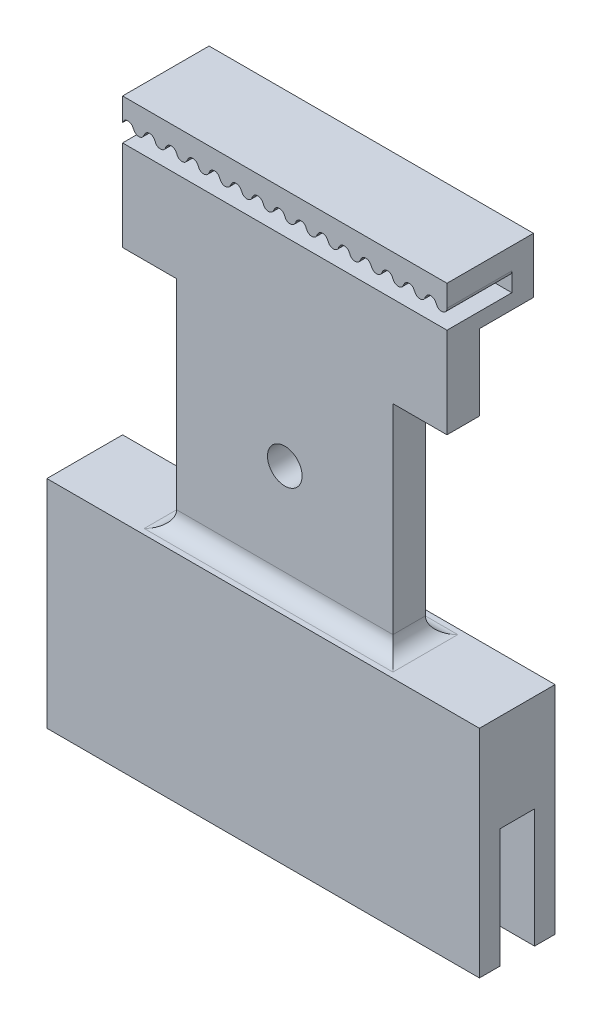
SolidWorks part; units mm, degrees
ref_plane "Ön Düzlem" through (0, 0, 0) normal (0, 0, 1) x (1, 0, 0)
ref_plane "Üst Düzlem" through (0, 0, 0) normal (0, 1, 0) x (1, 0, 0)
ref_plane "Sağ Düzlem" through (0, 0, 0) normal (1, 0, 0) x (0, 0, -1)
sketch "Çizim1" plane through (0, 0, 0) normal (0, 1, 0) x (1, 0, 0)
  line L1 (-20, -3.5) -> (20, -3.5)
  line L2 (-20, -3.5) -> (-20, 3.5)
  line L3 (-20, 3.5) -> (20, 3.5)
  line L4 (20, -3.5) -> (20, 3.5)
  line L5 (-20, -3.5) -> (20, 3.5) construction
  line L6 (-20, 3.5) -> (20, -3.5) construction
  point P1 (0, 0)
  dimension "D1" = 40
  dimension "D2" = 7
extrude "Yükseklik-Ekstrüzyon1" add sketch "Çizim1" against normal blind 20
sketch "Çizim2" plane through (0, -20, 0) normal (0, -1, 0) x (1, 0, 0)
  line L0 (20, 3.5) -> (20, -3.5) construction
  line L1 (-20, -1.6) -> (20, -1.6)
  line L2 (-20, -1.6) -> (-20, 1.6)
  line L3 (-20, 1.6) -> (20, 1.6)
  line L4 (20, -1.6) -> (20, 1.6)
  line L5 (-20, -1.6) -> (20, 1.6) construction
  line L6 (-20, 1.6) -> (20, -1.6) construction
  point P0 (0, 0)
  dimension "D1" = 3.2
extrude "Kes-Ekstrüzyon1" cut sketch "Çizim2" against normal blind 11
sketch "Çizim4" plane through (0, 0, 0) normal (0, 0, 1) x (1, 0, 0)
  line L0 (0, 0) -> (-10, 0) construction
  line L1 (-20, 0) -> (20, 0) construction
  line L2 (0, 0) -> (10, 0) construction
  line L3 (0, 0) -> (0, 10) construction
  line L4 (-10, 0) -> (10, 0)
  line L5 (-10, 0) -> (-10, 20)
  line L6 (-10, 20) -> (10, 20)
  line L7 (10, 0) -> (10, 20)
  circle A0 centre (0, 10) radius 1.6
  dimension "D2" = 3.2
  dimension "D1" = 20
  dimension "D3" = 10
extrude "Yükseklik-Ekstrüzyon2" add sketch "Çizim4" along normal blind 1.5 and the other way blind 1.5
fillet "Radyus1" radius 1.5 4 edges at (-10, 0, 0) (0, 0, -1.5) (10, 0, 0) (0, 0, 1.5)
ref_plane "Düzlem1" through (0, 0, -1.5) normal (0, 0, -1) x (-1, 0, 0)
sketch "Çizim7" plane through (0, 20, 0) normal (0, 1, 0) x (1, 0, 0)
  line L1 (-15, -1.5) -> (15, -1.5)
  line L2 (-15, -1.5) -> (-15, 1.5)
  line L3 (-15, 1.5) -> (15, 1.5)
  line L4 (15, -1.5) -> (15, 1.5)
  line L5 (-15, -1.5) -> (15, 1.5) construction
  line L6 (-15, 1.5) -> (15, -1.5) construction
  point P0 (0, 0)
  dimension "D1" = 3
  dimension "D2" = 30
extrude "Yükseklik-Ekstrüzyon4" add sketch "Çizim7" along normal blind 7
sketch "Çizim9" plane through (0, 0, -1.5) normal (0, 0, -1) x (-1, 0, 0)
  line L0 (0, 32.14) -> (-15, 32.14)
  line L1 (0, 32.14) -> (15, 32.14)
  line L2 (-15, 32.14) -> (-15, 29.64)
  line L3 (15, 32.14) -> (15, 29.64)
  line L4 (-15, 29.64) -> (15, 29.64)
  line L5 (-15, 30.39) -> (-14, 30.39)
  line L6 (-15, 30.39) -> (-15, 30.13)
  line L7 (-14.51, 29.64) -> (-14.49, 29.64)
  line L8 (-14, 30.39) -> (-14, 30.13)
  line L9 (-13, 30.39) -> (-12, 30.39)
  line L10 (-12, 30.39) -> (-12, 30.13)
  line L11 (-12.51, 29.64) -> (-12.49, 29.64)
  line L12 (-13, 30.39) -> (-13, 30.13)
  line L13 (-11, 30.39) -> (-10, 30.39)
  line L14 (-10, 30.39) -> (-10, 30.13)
  line L15 (-10.51, 29.64) -> (-10.49, 29.64)
  line L16 (-11, 30.39) -> (-11, 30.13)
  line L17 (-9, 30.39) -> (-8, 30.39)
  line L18 (-8, 30.39) -> (-8, 30.13)
  line L19 (-8.51, 29.64) -> (-8.49, 29.64)
  line L20 (-9, 30.39) -> (-9, 30.13)
  line L21 (-7, 30.39) -> (-6, 30.39)
  line L22 (-6, 30.39) -> (-6, 30.13)
  line L23 (-6.51, 29.64) -> (-6.49, 29.64)
  line L24 (-7, 30.39) -> (-7, 30.13)
  line L25 (-5, 30.39) -> (-4, 30.39)
  line L26 (-4, 30.39) -> (-4, 30.13)
  line L27 (-4.51, 29.64) -> (-4.49, 29.64)
  line L28 (-5, 30.39) -> (-5, 30.13)
  line L29 (-3, 30.39) -> (-2, 30.39)
  line L30 (-2, 30.39) -> (-2, 30.13)
  line L31 (-2.51, 29.64) -> (-2.49, 29.64)
  line L32 (-3, 30.39) -> (-3, 30.13)
  line L33 (-1, 30.39) -> (0, 30.39)
  line L34 (0, 30.39) -> (0, 30.13)
  line L35 (-0.51, 29.64) -> (-0.49, 29.64)
  line L36 (-1, 30.39) -> (-1, 30.13)
  line L37 (1, 30.39) -> (2, 30.39)
  line L38 (2, 30.39) -> (2, 30.13)
  line L39 (1.49, 29.64) -> (1.51, 29.64)
  line L40 (1, 30.39) -> (1, 30.13)
  line L41 (3, 30.39) -> (4, 30.39)
  line L42 (4, 30.39) -> (4, 30.13)
  line L43 (3.49, 29.64) -> (3.51, 29.64)
  line L44 (3, 30.39) -> (3, 30.13)
  line L45 (5, 30.39) -> (6, 30.39)
  line L46 (6, 30.39) -> (6, 30.13)
  line L47 (5.49, 29.64) -> (5.51, 29.64)
  line L48 (5, 30.39) -> (5, 30.13)
  line L49 (7, 30.39) -> (8, 30.39)
  line L50 (8, 30.39) -> (8, 30.13)
  line L51 (7.49, 29.64) -> (7.51, 29.64)
  line L52 (7, 30.39) -> (7, 30.13)
  line L53 (9, 30.39) -> (10, 30.39)
  line L54 (10, 30.39) -> (10, 30.13)
  line L55 (9.49, 29.64) -> (9.51, 29.64)
  line L56 (9, 30.39) -> (9, 30.13)
  line L57 (11, 30.39) -> (12, 30.39)
  line L58 (12, 30.39) -> (12, 30.13)
  line L59 (11.49, 29.64) -> (11.51, 29.64)
  line L60 (11, 30.39) -> (11, 30.13)
  line L61 (13, 30.39) -> (14, 30.39)
  line L62 (14, 30.39) -> (14, 30.13)
  line L63 (13.49, 29.64) -> (13.51, 29.64)
  line L64 (13, 30.39) -> (13, 30.13)
  line L65 (-5.51, 30.39) -> (-5.49, 30.39)
  line L66 (-6, 29.9) -> (-6, 29.64)
  line L67 (-6, 29.64) -> (-5, 29.64)
  line L68 (-5, 29.9) -> (-5, 29.64)
  line L69 (-3.51, 30.39) -> (-3.49, 30.39)
  line L70 (-3, 29.9) -> (-3, 29.64)
  line L71 (-4, 29.64) -> (-3, 29.64)
  line L72 (-4, 29.9) -> (-4, 29.64)
  line L73 (-1.51, 30.39) -> (-1.49, 30.39)
  line L74 (-1, 29.9) -> (-1, 29.64)
  line L75 (-2, 29.64) -> (-1, 29.64)
  line L76 (-2, 29.9) -> (-2, 29.64)
  line L77 (0.49, 30.39) -> (0.51, 30.39)
  line L78 (1, 29.9) -> (1, 29.64)
  line L79 (0, 29.64) -> (1, 29.64)
  line L80 (0, 29.9) -> (0, 29.64)
  line L81 (2.49, 30.39) -> (2.51, 30.39)
  line L82 (3, 29.9) -> (3, 29.64)
  line L83 (2, 29.64) -> (3, 29.64)
  line L84 (2, 29.9) -> (2, 29.64)
  line L85 (4.49, 30.39) -> (4.51, 30.39)
  line L86 (5, 29.9) -> (5, 29.64)
  line L87 (4, 29.64) -> (5, 29.64)
  line L88 (4, 29.9) -> (4, 29.64)
  line L89 (6.49, 30.39) -> (6.51, 30.39)
  line L90 (7, 29.9) -> (7, 29.64)
  line L91 (6, 29.64) -> (7, 29.64)
  line L92 (6, 29.9) -> (6, 29.64)
  line L93 (8.49, 30.39) -> (8.51, 30.39)
  line L94 (9, 29.9) -> (9, 29.64)
  line L95 (8, 29.64) -> (9, 29.64)
  line L96 (8, 29.9) -> (8, 29.64)
  line L97 (10.49, 30.39) -> (10.51, 30.39)
  line L98 (11, 29.9) -> (11, 29.64)
  line L99 (10, 29.64) -> (11, 29.64)
  line L100 (10, 29.9) -> (10, 29.64)
  line L101 (12.49, 30.39) -> (12.51, 30.39)
  line L102 (13, 29.9) -> (13, 29.64)
  line L103 (12, 29.64) -> (13, 29.64)
  line L104 (12, 29.9) -> (12, 29.64)
  line L105 (14.49, 30.39) -> (14.51, 30.39)
  line L106 (15, 29.9) -> (15, 29.64)
  line L107 (14, 29.64) -> (15, 29.64)
  line L108 (14, 29.9) -> (14, 29.64)
  line L109 (-7.51, 30.39) -> (-7.49, 30.39)
  line L110 (-7, 29.9) -> (-7, 29.64)
  line L111 (-8, 29.64) -> (-7, 29.64)
  line L112 (-8, 29.9) -> (-8, 29.64)
  line L113 (-9.51, 30.39) -> (-9.49, 30.39)
  line L114 (-9, 29.9) -> (-9, 29.64)
  line L115 (-10, 29.64) -> (-9, 29.64)
  line L116 (-10, 29.9) -> (-10, 29.64)
  line L117 (-11.51, 30.39) -> (-11.49, 30.39)
  line L118 (-11, 29.9) -> (-11, 29.64)
  line L119 (-12, 29.64) -> (-11, 29.64)
  line L120 (-12, 29.9) -> (-12, 29.64)
  line L121 (-13.51, 30.39) -> (-13.49, 30.39)
  line L122 (-13, 29.9) -> (-13, 29.64)
  line L123 (-14, 29.64) -> (-13, 29.64)
  line L124 (-14, 29.9) -> (-14, 29.64)
  line L125 (-13.9826, 30.0293) -> (-14.0105, 30.0293)
  line L126 (-11.9826, 30.0293) -> (-12.0105, 30.0293)
  line L127 (-9.9826, 30.0293) -> (-10.0105, 30.0293)
  line L128 (-7.9826, 30.0293) -> (-8.0105, 30.0293)
  line L129 (-5.9826, 30.0293) -> (-6.0105, 30.0293)
  line L130 (-3.9826, 30.0293) -> (-4.0105, 30.0293)
  line L131 (-1.9826, 30.0293) -> (-2.0105, 30.0293)
  line L132 (0.0174, 30.0293) -> (-0.0105, 30.0293)
  line L133 (2.0174, 30.0293) -> (1.9895, 30.0293)
  line L134 (4.0174, 30.0293) -> (3.9895, 30.0293)
  line L135 (6.0174, 30.0293) -> (5.9895, 30.0293)
  line L136 (8.0174, 30.0293) -> (7.9895, 30.0293)
  line L137 (10.0174, 30.0293) -> (9.9895, 30.0293)
  line L138 (12.0174, 30.0293) -> (11.9895, 30.0293)
  line L139 (14.0174, 30.0293) -> (13.9895, 30.0293)
  line L140 (-13.0174, 30.0293) -> (-12.9895, 30.0293)
  line L141 (-11.0174, 30.0293) -> (-10.9895, 30.0293)
  line L142 (-9.0174, 30.0293) -> (-8.9895, 30.0293)
  line L143 (-7.0174, 30.0293) -> (-6.9895, 30.0293)
  line L144 (-5.0174, 30.0293) -> (-4.9895, 30.0293)
  line L145 (-3.0174, 30.0293) -> (-2.9895, 30.0293)
  line L146 (-1.0174, 30.0293) -> (-0.9895, 30.0293)
  line L147 (0.9826, 30.0293) -> (1.0105, 30.0293)
  line L148 (2.9826, 30.0293) -> (3.0105, 30.0293)
  line L149 (4.9826, 30.0293) -> (5.0105, 30.0293)
  line L150 (6.9826, 30.0293) -> (7.0105, 30.0293)
  line L151 (8.9826, 30.0293) -> (9.0105, 30.0293)
  line L152 (10.9826, 30.0293) -> (11.0105, 30.0293)
  line L153 (12.9826, 30.0293) -> (13.0105, 30.0293)
  line L154 (14.9826, 30.0293) -> (15.0105, 30.0293)
  line L155 (-15, 27) -> (-15, 28.38)
  line L156 (0, 27) -> (-15, 27)
  line L157 (0, 27) -> (15, 27)
  line L158 (15, 27) -> (15, 28.38)
  line L159 (-15, 28.38) -> (15, 28.38)
  line L160 (-16.7921, 31.51) -> (-16.7921, 27) construction
  line L161 (-15, 28.38) -> (-16.7921, 28.38) construction
  line L162 (-17.2226, 28.38) -> (-17.2226, 30.58) construction
  line L163 (-17.2226, 30.58) -> (18.4338, 30.58) construction
  line L164 (16.139, 30.58) -> (16.139, 28.38) construction
  line L165 (16.6815, 28.38) -> (16.6815, 30.48) construction
  arc A0 (-14.49, 29.64) -> (-14, 30.13) centre (-14.49, 30.13) ccw
  arc A1 (-15, 30.13) -> (-14.51, 29.64) centre (-14.51, 30.13) ccw
  arc A2 (-12.49, 29.64) -> (-12, 30.13) centre (-12.49, 30.13) ccw
  arc A3 (-13, 30.13) -> (-12.51, 29.64) centre (-12.51, 30.13) ccw
  arc A4 (-10.49, 29.64) -> (-10, 30.13) centre (-10.49, 30.13) ccw
  arc A5 (-11, 30.13) -> (-10.51, 29.64) centre (-10.51, 30.13) ccw
  arc A6 (-8.49, 29.64) -> (-8, 30.13) centre (-8.49, 30.13) ccw
  arc A7 (-9, 30.13) -> (-8.51, 29.64) centre (-8.51, 30.13) ccw
  arc A8 (-6.49, 29.64) -> (-6, 30.13) centre (-6.49, 30.13) ccw
  arc A9 (-7, 30.13) -> (-6.51, 29.64) centre (-6.51, 30.13) ccw
  arc A10 (-4.49, 29.64) -> (-4, 30.13) centre (-4.49, 30.13) ccw
  arc A11 (-5, 30.13) -> (-4.51, 29.64) centre (-4.51, 30.13) ccw
  arc A12 (-2.49, 29.64) -> (-2, 30.13) centre (-2.49, 30.13) ccw
  arc A13 (-3, 30.13) -> (-2.51, 29.64) centre (-2.51, 30.13) ccw
  arc A14 (-0.49, 29.64) -> (0, 30.13) centre (-0.49, 30.13) ccw
  arc A15 (-1, 30.13) -> (-0.51, 29.64) centre (-0.51, 30.13) ccw
  arc A16 (1.51, 29.64) -> (2, 30.13) centre (1.51, 30.13) ccw
  arc A17 (1, 30.13) -> (1.49, 29.64) centre (1.49, 30.13) ccw
  arc A18 (3.51, 29.64) -> (4, 30.13) centre (3.51, 30.13) ccw
  arc A19 (3, 30.13) -> (3.49, 29.64) centre (3.49, 30.13) ccw
  arc A20 (5.51, 29.64) -> (6, 30.13) centre (5.51, 30.13) ccw
  arc A21 (5, 30.13) -> (5.49, 29.64) centre (5.49, 30.13) ccw
  arc A22 (7.51, 29.64) -> (8, 30.13) centre (7.51, 30.13) ccw
  arc A23 (7, 30.13) -> (7.49, 29.64) centre (7.49, 30.13) ccw
  arc A24 (9.51, 29.64) -> (10, 30.13) centre (9.51, 30.13) ccw
  arc A25 (9, 30.13) -> (9.49, 29.64) centre (9.49, 30.13) ccw
  arc A26 (11.51, 29.64) -> (12, 30.13) centre (11.51, 30.13) ccw
  arc A27 (11, 30.13) -> (11.49, 29.64) centre (11.49, 30.13) ccw
  arc A28 (13.51, 29.64) -> (14, 30.13) centre (13.51, 30.13) ccw
  arc A29 (13, 30.13) -> (13.49, 29.64) centre (13.49, 30.13) ccw
  arc A30 (-5.49, 30.39) -> (-5, 29.9) centre (-5.49, 29.9) cw
  arc A31 (-5.51, 30.39) -> (-6, 29.9) centre (-5.51, 29.9) ccw
  arc A32 (-3.51, 30.39) -> (-4, 29.9) centre (-3.51, 29.9) ccw
  arc A33 (-3.49, 30.39) -> (-3, 29.9) centre (-3.49, 29.9) cw
  arc A34 (-1.51, 30.39) -> (-2, 29.9) centre (-1.51, 29.9) ccw
  arc A35 (-1.49, 30.39) -> (-1, 29.9) centre (-1.49, 29.9) cw
  arc A36 (0.49, 30.39) -> (0, 29.9) centre (0.49, 29.9) ccw
  arc A37 (0.51, 30.39) -> (1, 29.9) centre (0.51, 29.9) cw
  arc A38 (2.49, 30.39) -> (2, 29.9) centre (2.49, 29.9) ccw
  arc A39 (2.51, 30.39) -> (3, 29.9) centre (2.51, 29.9) cw
  arc A40 (4.49, 30.39) -> (4, 29.9) centre (4.49, 29.9) ccw
  arc A41 (4.51, 30.39) -> (5, 29.9) centre (4.51, 29.9) cw
  arc A42 (6.49, 30.39) -> (6, 29.9) centre (6.49, 29.9) ccw
  arc A43 (6.51, 30.39) -> (7, 29.9) centre (6.51, 29.9) cw
  arc A44 (8.49, 30.39) -> (8, 29.9) centre (8.49, 29.9) ccw
  arc A45 (8.51, 30.39) -> (9, 29.9) centre (8.51, 29.9) cw
  arc A46 (10.49, 30.39) -> (10, 29.9) centre (10.49, 29.9) ccw
  arc A47 (10.51, 30.39) -> (11, 29.9) centre (10.51, 29.9) cw
  arc A48 (12.49, 30.39) -> (12, 29.9) centre (12.49, 29.9) ccw
  arc A49 (12.51, 30.39) -> (13, 29.9) centre (12.51, 29.9) cw
  arc A50 (14.49, 30.39) -> (14, 29.9) centre (14.49, 29.9) ccw
  arc A51 (14.51, 30.39) -> (15, 29.9) centre (14.51, 29.9) cw
  arc A52 (-7.51, 30.39) -> (-8, 29.9) centre (-7.51, 29.9) ccw
  arc A53 (-7.49, 30.39) -> (-7, 29.9) centre (-7.49, 29.9) cw
  arc A54 (-9.51, 30.39) -> (-10, 29.9) centre (-9.51, 29.9) ccw
  arc A55 (-9.49, 30.39) -> (-9, 29.9) centre (-9.49, 29.9) cw
  arc A56 (-11.51, 30.39) -> (-12, 29.9) centre (-11.51, 29.9) ccw
  arc A57 (-11.49, 30.39) -> (-11, 29.9) centre (-11.49, 29.9) cw
  arc A58 (-13.51, 30.39) -> (-14, 29.9) centre (-13.51, 29.9) ccw
  arc A59 (-13.49, 30.39) -> (-13, 29.9) centre (-13.49, 29.9) cw
  dimension "D1" = 2.5
extrude "Yükseklik-Ekstrüzyon6" add sketch "Çizim9" against normal blind 3 and the other way blind 3 contours L64 A29 L4 A28 L62 L61 | L60 A27 L4 A26 L58 L57 | L56 A25 L4 A24 L54 L53 | L52 A23 L4 A22 L50 L49 | L48 A21 L4 A20 L46 L45 | L44 A19 L4 A18 L42 L41 | L40 A17 L4 A16 L38 L37 | L36 A15 L4 A14 L34 L33 | L32 A13 L4 A12 L30 L29 | L28 A11 L4 A10 L26 L25 | L24 A9 L4 A8 L22 L21 | L20 A7 L4 A6 L18 L17 | L16 A5 L4 A4 L14 L13 | L12 A3 L4 A2 L10 L9 | L2 A1 L4 A0 L8 L5 | L159 L155 L156 L157 L158 | L121 A59 L140 A3 L12 L9 L10 A2 L126 A56 L117 A57 L141 A5 L16 L13 L14 A4 L127 A54 L113 A55 L142 A7 L20 L17 L18 A6 L128 A52 L109 A53 L143 A9 L24 L21 L22 A8 L129 A31 L65 A30 L144 A11 L28 L25 L26 A10 L130 A32 L69
sketch "Çizim10" plane through (0, 0, -4.5) normal (0, 0, -1) x (-1, 0, 0)
  line L1 (-15, 27) -> (15, 27)
  line L2 (-15, 27) -> (-15, 32.14)
  line L3 (-15, 32.14) -> (15, 32.14)
  line L4 (15, 27) -> (15, 32.14)
extrude "Yükseklik-Ekstrüzyon7" add sketch "Çizim10" along normal blind 2
